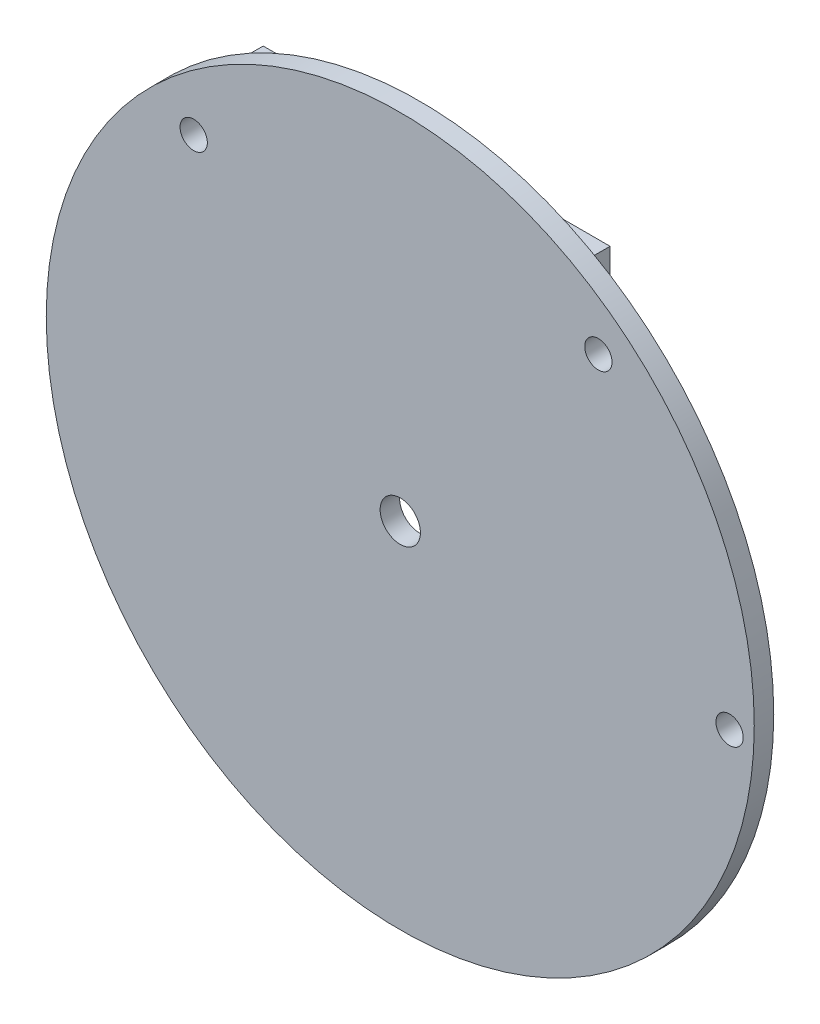
SolidWorks part; units mm, degrees
ref_plane "Front Plane" through (0, 0, 0) normal (0, 0, 1) x (1, 0, 0)
ref_plane "Top Plane" through (0, 0, 0) normal (0, 1, 0) x (1, 0, 0)
ref_plane "Right Plane" through (0, 0, 0) normal (1, 0, 0) x (0, 0, -1)
sketch "Эскиз1" plane through (0, 0, 0) normal (0, 0, 1) x (1, 0, 0)
  line L0 (0, 0) -> (0, 17.8)
  line L1 (0, 17.8) -> (-15.9, 17.8)
  line L2 (0, 17.8) -> (0, 18.75)
  line L3 (0, 18.75) -> (15.25, 18.75)
  line L4 (0, 0) -> (0, -1.23)
  line L5 (0, -1.23) -> (25.35, -1.23)
  circle A0 centre (0, 0) radius 27.25
  circle A1 centre (-15.9, 17.8) radius 1.05
  circle A2 centre (15.25, 18.75) radius 1.05
  circle A3 centre (25.35, -1.23) radius 1.05
  circle A5 centre (0, 0) radius 1.55
  dimension "D7" = 54.5
  dimension "D8" = 2.1
  dimension "D9" = 3.1
  dimension "D1" = 15.9
  dimension "D2" = 15.25
  dimension "D3" = 18.75
  dimension "D4" = 17.8
  dimension "D5" = 1.23
  dimension "D6" = 25.35
extrude "Бобышка-Вытянуть1" add sketch "Эскиз1" along normal blind 1.5
sketch "Эскиз2" plane through (0, 0, 0) normal (0, 0, 1) x (1, 0, 0)
  line L0 (0, 0) -> (0, 14)
  line L1 (-13.35, 4.4) -> (13.35, 4.4)
  line L2 (-13.35, 4.4) -> (-13.35, 23.6)
  line L3 (-13.35, 23.6) -> (13.35, 23.6)
  line L4 (13.35, 4.4) -> (13.35, 23.6)
  line L5 (-13.35, 4.4) -> (13.35, 23.6) construction
  line L6 (-13.35, 23.6) -> (13.35, 4.4) construction
  point P0 (0, 14)
  dimension "D1" = 19.2
  dimension "D2" = 26.7
  dimension "D3" = 14
extrude "Бобышка-Вытянуть2" add sketch "Эскиз2" against normal blind 1.3
sketch "Sketch1" plane through (0, 0, 0) normal (0, 0, -1) x (-1, 0, 0)
  line L0 (0, 0) -> (15.5395, 10.2853) construction
  line L1 (19.0478, 14.4062) -> (20.7036, 11.9046)
  line L2 (19.0478, 14.4062) -> (14.7116, 11.5362)
  line L3 (14.7116, 11.5362) -> (16.3674, 9.0345)
  line L4 (20.7036, 11.9046) -> (16.3674, 9.0345)
  line L5 (0, 0) -> (0, 42.7139) construction
  dimension "D1" = 5.2
  dimension "D2" = 3
  dimension "D3" = 18.635
  dimension "D4" = 56.5
extrude "Boss-Extrude1" add sketch "Sketch1" along normal blind 1
pattern_circular "CirPattern1" count 9 every 14.5 about axis through (0, 0, 0) along (0, 0, 1) of "Boss-Extrude1"
sketch "Sketch2" plane through (0, 0, 0) normal (0, 0, -1) x (-1, 0, 0)
  line L0 (2.4, 0) -> (0, 0) construction
  line L1 (1.23, -4.36) -> (-1.23, -4.36)
  line L2 (1.23, -4.36) -> (1.23, -2.4)
  line L3 (1.23, -2.4) -> (-1.23, -2.4)
  line L4 (-1.23, -4.36) -> (-1.23, -2.4)
  line L5 (-2.4, -1.23) -> (-4.36, -1.23)
  line L6 (-2.4, -1.23) -> (-2.4, 1.23)
  line L7 (-2.4, 1.23) -> (-4.36, 1.23)
  line L8 (-4.36, -1.23) -> (-4.36, 1.23)
  line L9 (4.36, -1.23) -> (2.4, -1.23)
  line L10 (4.36, -1.23) -> (4.36, 1.23)
  line L11 (4.36, 1.23) -> (2.4, 1.23)
  line L12 (2.4, -1.23) -> (2.4, 1.23)
  line L13 (0, 0) -> (-2.4, 0) construction
  line L14 (0, 0) -> (0, -2.4) construction
  dimension "D3" = 2.4
  dimension "D1" = 1.96
  dimension "D2" = 2.46
extrude "Boss-Extrude2" add sketch "Sketch2" along normal blind 0.8
mirror "Mirror1" about plane through (0, 0, 0) normal (1, 0, 0) of "CirPattern1", "Boss-Extrude1"
